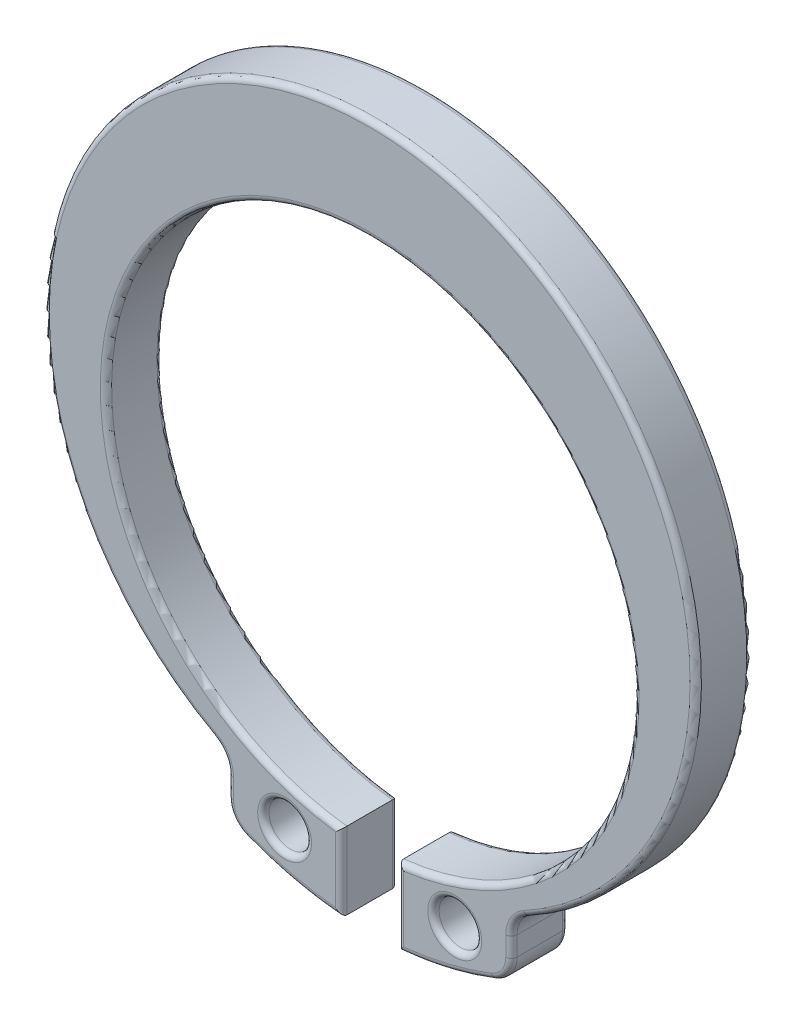
SolidWorks part; units mm, degrees
ref_plane "前视基准面" through (0, 0, 0) normal (0, 0, 1) x (1, 0, 0)
ref_plane "上视基准面" through (0, 0, 0) normal (0, 1, 0) x (1, 0, 0)
ref_plane "右视基准面" through (0, 0, 0) normal (1, 0, 0) x (0, 0, -1)
other "Configuration Table"
sketch "草图1" plane through (0, 0, 0) normal (0, 0, 1) x (1, 0, 0)
  line L0 (0, 0) -> (0, 6.45) construction
  circle A0 centre (0, 0) radius 4.65
  circle A1 centre (0, 0.7) radius 5.75
  point P7 (0, 4.65)
  point P8 (0, 6.45)
  dimension "D2" = 9.3
  dimension "D3" = 11.5
  dimension "D1" = 1.8
extrude "凸台-拉伸1" add sketch "草图1" along normal blind 1
sketch "草图3" plane through (0, 0, 0) normal (0, 0, 1) x (1, 0, 0)
  line L0 (0, 0) -> (0, -6) construction
  line L1 (2.5, -4.4781) -> (2.5, -5.4544)
  line L2 (-2.5, -4.4781) -> (-2.5, -5.4544)
  arc A0 (-2.5, -5.4544) -> (2.5, -5.4544) centre (0, 0) ccw
  circle A2 centre (0, 0.7) radius 5.75 construction
  arc A3 (-2.5, -4.4781) -> (2.5, -4.4781) centre (0, 0.7) ccw
  dimension "D1" = 12
  dimension "D2" = 5
extrude "凸台-拉伸2" add sketch "草图3" along normal blind 1
sketch "草图4" plane through (0, 0, 1) normal (0, 0, 1) x (1, 0, 0)
  line L0 (0, -4.65) -> (0, -6) construction
  line L1 (-1.5, -5.1) -> (1.5, -5.1) construction
  line L2 (-0.5, -6.027) -> (0.5, -6.027)
  line L3 (-0.5, -6.027) -> (-0.5, -4.623)
  line L4 (-0.5, -4.623) -> (0.5, -4.623)
  line L5 (0.5, -6.027) -> (0.5, -4.623)
  line L6 (-0.5, -6.027) -> (0.5, -4.623) construction
  line L7 (-0.5, -4.623) -> (0.5, -6.027) construction
  circle A1 centre (1.5, -5.1) radius 0.375
  circle A2 centre (-1.5, -5.1) radius 0.375
  circle A3 centre (0, 0) radius 4.65 construction
  arc A4 (-2.5, -5.4544) -> (2.5, -5.4544) centre (0, 0) ccw construction
  point P11 (0, -5.325)
  dimension "D1" = 0.75
  dimension "D2" = 3
  dimension "D3" = 1
  dimension "D4" = 5.1
extrude "切除-拉伸1" cut sketch "草图4" against normal blind 1
fillet "圆角3" radius 0.5 4 edges at (2.5, -5.4544, 0.5) (2.5, -4.4781, 0.5) (-2.5, -5.4544, 0.5) (-2.5, -4.4781, 0.5)
fillet "圆角2" radius 0.1 28 edges at (2.5, -4.9532, 1) (2.5, -4.9532, 0) (0, 6.45, 0) (-2.5, -4.9532, 0) (-2.5, -4.9532, 1) (-1.355, -5.845, 1) (-1.355, -5.845, 0) (-0.5, -5.3011, 0) (0, 4.65, 0) (0.5, -5.3011, 0) (1.355, -5.845, 0) (1.355, -5.845, 1) (-1.875, -5.1, 0) (1.875, -5.1, 0) (0, 4.65, 1) (-0.5, -5.3011, 1) (0, 6.45, 1) (0.5, -5.3011, 1) (-1.875, -5.1, 1) (1.875, -5.1, 1) (2.5699, -4.528, 0) (-2.5699, -4.528, 0) (-2.4129, -5.4055, 0) (2.4129, -5.4055, 0) (-2.4129, -5.4055, 1) (-2.5699, -4.528, 1) (2.5699, -4.528, 1) (2.4129, -5.4055, 1)
